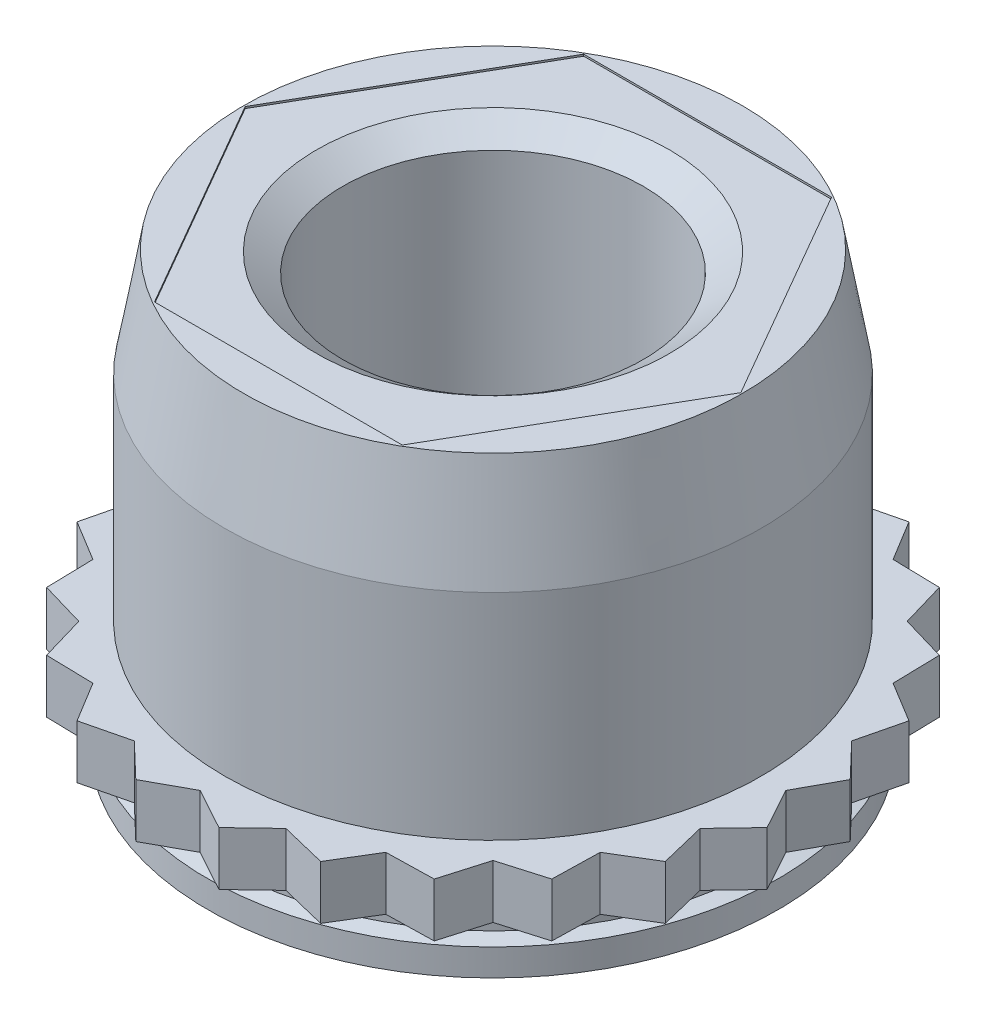
SolidWorks part; units mm, degrees
revolve "Body" add sketch "BodySke"
sketch "BodySke" plane through (0, 0, 0) normal (0, 0, 1) x (1, 0, 0)
  line L0 (3.7857, -1.0716) -> (3.7858, -0.75)
  line L1 (3.75, 3) -> (3.4855, 4.5)
  line L2 (4.45, 0) -> (3.75, 0)
  line L3 (2.1, 4.5) -> (2.1, -1.5)
  line L4 (2.1, -1.5) -> (3.985, -1.5)
  line L5 (3.985, -1.5) -> (3.985, -1.125)
  line L6 (3.985, -1.125) -> (3.7857, -1.0716)
  line L7 (1.016, 0.8) -> (3.75, 0.8) construction
  line L8 (3.75, 0) -> (3.75, 3)
  line L9 (0, 0) -> (0, 15.24) construction
  line L11 (3.4855, 4.5) -> (2.1, 4.5)
  line L15 (3.7858, -0.75) -> (4.45, -0.75)
  line L16 (4.45, -0.75) -> (4.45, 0)
  dimension "Clinch_dia" = 8.9
  dimension "C_dia" = 7.97
  dimension "Thread_min" = 4.2
  dimension "Advance" = 0.8
  dimension "D_dia" = 7.5
  dimension "Height" = 4.5
  dimension "A_ht" = 1.5
  dimension "Clinching_ht" = 0.75
  dimension "Groove_dia" = 7.5715
  dimension "Chamfer_ht" = 1.5
  dimension "D1" = 10
  dimension "D2" = 75
  dimension "C_len" = 0.375
cosmetic thread "ThreadCosmetic" [suppressed]
revolve "EndChamfer" cut sketch "EndChamferSke" angle 360 about L0
sketch "EndChamferSke" plane through (0, 0, 0) normal (0, 0, 1) x (1, 0, 0)
  line L0 (0, -2.54) -> (0, 7.62) construction
  line L1 (0, 0) -> (0, 15.24) construction
  line L2 (2.5, -1.754) -> (2.5, -1.4975)
  line L3 (2.5, -1.4975) -> (2.1, -1.2175)
  line L4 (2.1, -1.2175) -> (2.1, -1.754)
  line L5 (2.1, -1.754) -> (2.5, -1.754)
  line L6 (2.5, 4.4975) -> (2.5, 4.754)
  line L7 (2.5, 4.754) -> (2.1, 4.754)
  line L8 (2.1, 4.754) -> (2.1, 4.2175)
  line L9 (2.1, 4.2175) -> (2.5, 4.4975)
  line L10 (3.4855, 4.5) -> (-3.4855, 4.5) construction
  line L11 (-3.985, -1.5) -> (3.985, -1.5) construction
  line L12 (2.1, 4.5) -> (-2.1, 4.5) construction
  dimension "Thread_nominal" = 5
  dimension "Thread_min" = 4.2
  dimension "D1" = 0.254
  dimension "D2" = 34.99
  dimension "D3" = 0.254
ref_plane "Plane1" through (0, 0, 0) normal (0, 0, 1) x (1, 0, 0)
ref_plane "Plane2" through (0, 0, 0) normal (0, 1, 0) x (1, 0, 0)
ref_plane "Plane3" through (0, 0, 0) normal (1, 0, 0) x (0, 0, -1)
ref_plane "Plane4" through (0, -0.5486, 0) normal (0, 1, 0) x (-1, 0, 0)
sketch "ThdSchSke" plane through (0, 0, 0) normal (0, 0, 1) x (1, 0, 0)
  line L0 (0, -5.08) -> (0, 7.62) construction
  line L1 (0, 0) -> (0, 15.24) construction
  line L2 (0, -1.4975) -> (2.5, -1.4975) construction
  line L4 (2.5, -1.4975) -> (2.1, -1.2174)
  line L6 (2.5, -1.4975) -> (2.1, -1.7775)
  line L7 (2.1, -1.2174) -> (2.1, -1.7775)
  line L8 (2.5, -1.4975) -> (-2.5, -1.4975) construction
  dimension "Thread_nominal" = 5
  dimension "Thread_min" = 4.2
revolve "ThreadSchematic" [suppressed] cut sketch "ThdSchSke" angle 360 about L0
pattern_linear "ThdSchPat" [suppressed]
sketch "CliRinCutSke" plane through (0, -0.75, 0) normal (0, -1, 0) x (1, 0, 0)
  line L0 (0.5808, 4.4119) -> (0, 4.094)
  line L1 (0, 4.094) -> (-0.5808, 4.4119)
  line L2 (0, 0) -> (0, 5.842) construction
  arc A1 (0.5808, 4.4119) -> (-0.5808, 4.4119) centre (0, 0) ccw
  circle A2 centre (0, 0) radius 4.094 construction
  dimension "Angle" = 15
  dimension "Clinch_dia" = 8.9
  dimension "Clinch_minor" = 8.188
extrude "ClinchCut" cut sketch "CliRinCutSke" against normal blind 0.75
pattern_circular "ClinchCutPat" count 24 every 15 about axis through (0, 0, 0) along (0, 1, 0) of "ClinchCut"
sketch "HexCutSke" plane through (0, 4.5, 0) normal (0, 1, 0) x (-1, 0, 0)
  line L0 (-1.7321, 3) -> (1.7321, 3)
  line L1 (1.7321, 3) -> (3.4641, 0)
  line L2 (3.4641, 0) -> (1.7321, -3)
  line L3 (1.7321, -3) -> (-1.7321, -3)
  line L4 (-1.7321, -3) -> (-3.4641, 0)
  line L5 (-3.4641, 0) -> (-1.7321, 3)
  circle A0 centre (0, 0) radius 3.4641 construction
  circle A1 centre (0, 0) radius 3 construction
  dimension "Width_across_flats" = 6
extrude "HexCut" cut sketch "HexCutSke" against normal blind 0.0254
equation "' \"A_ht@BodySke\" = 1.5"
equation "' \"C_dia@BodySke\" = 7.97"
equation "' \"D_dia@BodySke\" = 7.5"
equation "' \"Clinch_dia@BodySke\" = 8.9"
equation "' \"Height@BodySke\" = 4.5"
equation "' \"Advance@BodySke\" = 0.8"
equation "' \"Thread_min@BodySke\" = 4.2"
equation "' \"Thread_nominal@ThreadCosmetic\" = 5"
equation "\"Width_across_flats@HexCutSke\" = \"Thread_nominal@ThreadCosmetic\" * 1.2"
equation "\"Count@ClinchCutPat\" = 24"
equation "\"Angle@ClinchCutPat\" = 360 / \"Count@ClinchCutPat\""
equation "\"Angle@CliRinCutSke\" = 360 / \"Count@ClinchCutPat\""
equation "\"Clinch_dia@CliRinCutSke\" = \"Clinch_dia@BodySke\""
equation "\"Clinch_minor@CliRinCutSke\" = \"Clinch_dia@BodySke\" * 0.92"
equation "\"C_len@BodySke\" = \"A_ht@BodySke\" * 0.25"
equation "\"Groove_dia@BodySke\" = \"C_dia@BodySke\" * 0.95"
equation "\"Clinching_ht@BodySke\" = \"A_ht@BodySke\" * 0.5"
equation "\"Depth@ClinchCut\" =  \"A_ht@BodySke\" * 0.5"
equation "\"Chamfer_ht@BodySke\" = \"Height@BodySke\" / 3"
equation "\"Thread_nominal@EndChamferSke\" = \"Thread_nominal@ThreadCosmetic\""
equation "\"Thread_min@EndChamferSke\" = \"Thread_min@BodySke\""
equation "\"D2@EndChamferSke\" = \"Vee_angle@ThdSchSke\" / 2 - 0.01"
equation "\"Thread_nominal@ThdSchSke\" = \"Thread_nominal@ThreadCosmetic\""
equation "\"Thread_min@ThdSchSke\" = \"Thread_min@BodySke\""
equation "\"Num_threads@ThdSchPat\" = int(  ( \"Height@BodySke\" + \"A_ht@BodySke\" - \"Inset@EndChamferSke\" - \"Inset_far@EndChamferSke\" ) / \"Advance@BodySke\" + 0.999 )  + 1"
equation "\"Advance@ThdSchPat\" = ( \"Height@BodySke\" + \"A_ht@BodySke\" - \"Inset@EndChamferSke\" - \"Inset_far@EndChamferSke\" ) /  (\"Num_threads@ThdSchPat\" - 1) 'relax it"
